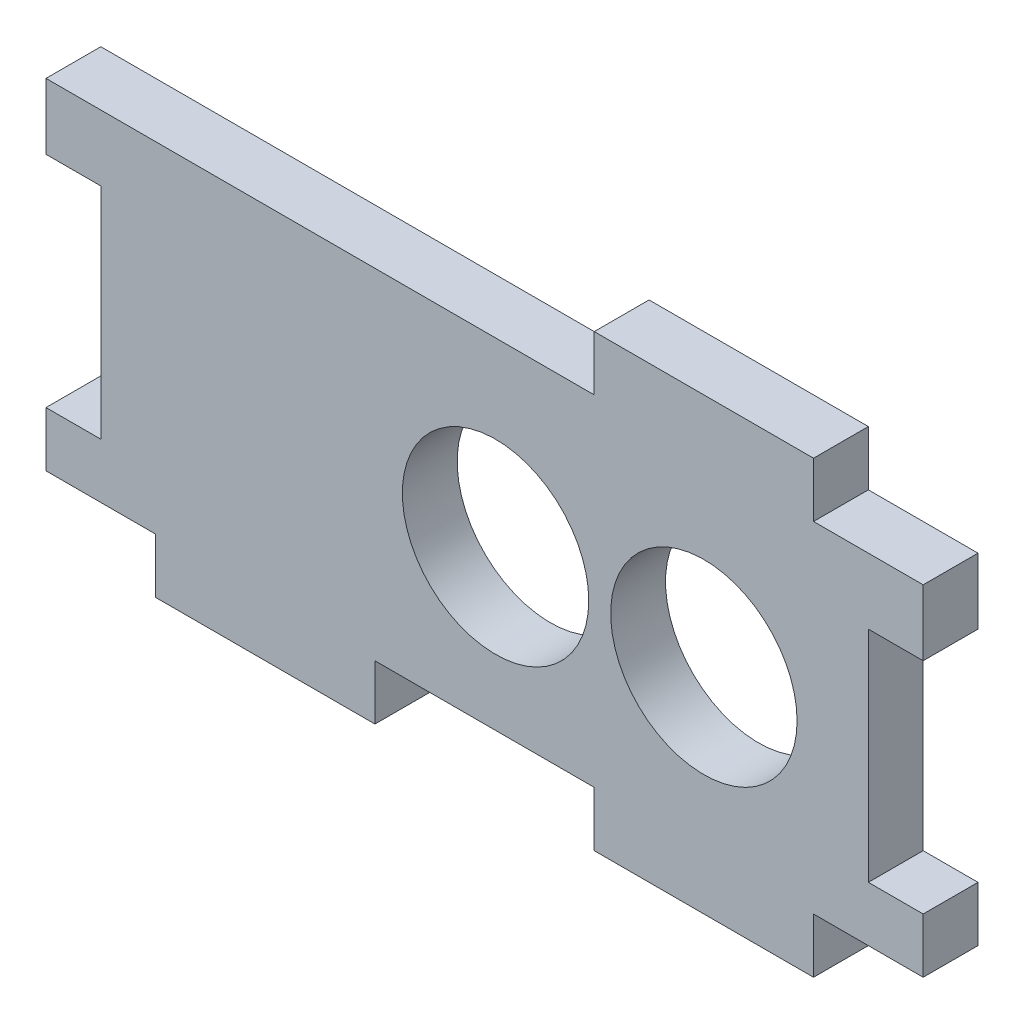
SolidWorks part; units mm, degrees
ref_plane "Front Plane" through (0, 0, 0) normal (0, 0, 1) x (1, 0, 0)
ref_plane "Top Plane" through (0, 0, 0) normal (0, 1, 0) x (1, 0, 0)
ref_plane "Right Plane" through (0, 0, 0) normal (1, 0, 0) x (0, 0, -1)
sketch "Sketch2" plane through (0, 0, 0) normal (0, 0, 1) x (1, 0, 0)
  line L0 (0, 31) -> (0, 14.5)
  line L1 (0, 0) -> (80, 0)
  line L2 (0, 0) -> (0, 31)
  line L3 (0, 31) -> (80, 31)
  line L4 (80, 0) -> (80, 31)
  line L5 (0, 14.5) -> (80, 14.5)
  line L6 (0, 14.5) -> (19, 14.5)
  line L7 (19, 14.5) -> (41, 14.5)
  line L8 (41, 14.5) -> (60, 14.5)
  line L10 (0, 5) -> (5, 5)
  line L11 (0, 5) -> (0, 25)
  line L12 (0, 25) -> (5, 25)
  line L13 (5, 5) -> (5, 25)
  line L14 (10, 31) -> (30, 31)
  line L15 (10, 31) -> (10, 26)
  line L16 (10, 26) -> (30, 26)
  line L17 (30, 31) -> (30, 26)
  line L18 (50, 31) -> (70, 31)
  line L19 (70, 31) -> (70, 36)
  line L20 (50, 31) -> (50, 36)
  line L22 (80, 25) -> (75, 25)
  line L23 (80, 25) -> (80, 5)
  line L24 (80, 5) -> (75, 5)
  line L25 (75, 25) -> (75, 5)
  line L26 (70, 0) -> (50, 0)
  line L27 (70, 0) -> (70, -5)
  line L28 (70, -5) -> (50, -5)
  line L29 (50, 0) -> (50, -5)
  line L30 (30, 0) -> (10, 0)
  line L31 (30, 0) -> (30, -5)
  line L32 (30, -5) -> (10, -5)
  line L33 (10, 0) -> (10, -5)
  line L36 (5, 28) -> (5, 31)
  line L37 (0, 28) -> (5, 28)
  line L38 (0, 28) -> (0, 23)
  line L39 (0, 23) -> (5, 23)
  line L40 (5, 28) -> (5, 23)
  line L41 (80, 28) -> (75, 28)
  line L42 (80, 28) -> (80, 23)
  line L43 (80, 23) -> (75, 23)
  line L44 (75, 28) -> (75, 23)
  line L45 (75, 28) -> (75, 31)
  line L49 (50, 36) -> (70, 36)
  circle A0 centre (60, 14.5) radius 8.5
  circle A1 centre (41, 14.5) radius 8.5
  dimension "D6" = 5
  dimension "D7" = 20
  dimension "D8" = 17
  dimension "D29" = 17
  dimension "D1" = 80
  dimension "D2" = 31
  dimension "D3" = 19
  dimension "D4" = 22
  dimension "D5" = 19
  dimension "D9" = 20
  dimension "D10" = 5
  dimension "D11" = 20
  dimension "D12" = 5
  dimension "D13" = 5
  dimension "D14" = 5
  dimension "D15" = 20
  dimension "D16" = 20
  dimension "D17" = 5
  dimension "D18" = 5
  dimension "D19" = 10
  dimension "D20" = 10
  dimension "D21" = 20
  dimension "D22" = 10
  dimension "D23" = 16.5
  dimension "D24" = 5
  dimension "D25" = 10
  dimension "D26" = 16.5
  dimension "D27" = 5
  dimension "D32" = 5
  dimension "D34" = 3
  dimension "D35" = 3
  dimension "D36" = 5
  dimension "D37" = 5
extrude "Boss-Extrude1" add sketch "Sketch2" against normal blind 5
